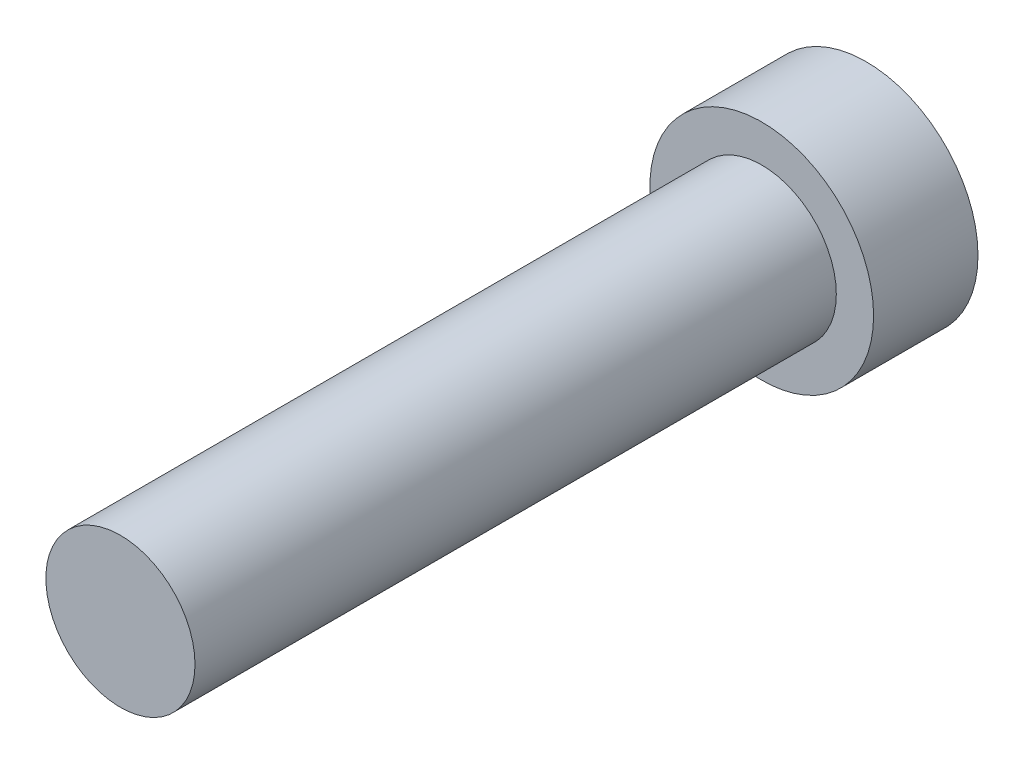
SolidWorks part; units mm, degrees
ref_plane "Front Plane" through (0, 0, 0) normal (0, 0, 1) x (1, 0, 0)
ref_plane "Top Plane" through (0, 0, 0) normal (0, 1, 0) x (1, 0, 0)
ref_plane "Right Plane" through (0, 0, 0) normal (1, 0, 0) x (0, 0, -1)
sketch "Sketch1" plane through (0, 0, 0) normal (0, 0, 1) x (1, 0, 0)
  circle A1 centre (0, 0) radius 7.5
extrude "Boss-Extrude1" add sketch "Sketch1" along normal blind 7
sketch "Sketch2" plane through (0, 0, 7) normal (0, 0, 1) x (1, 0, 0)
  circle A0 centre (0, 0) radius 5
extrude "Boss-Extrude2" add sketch "Sketch2" along normal blind 43
